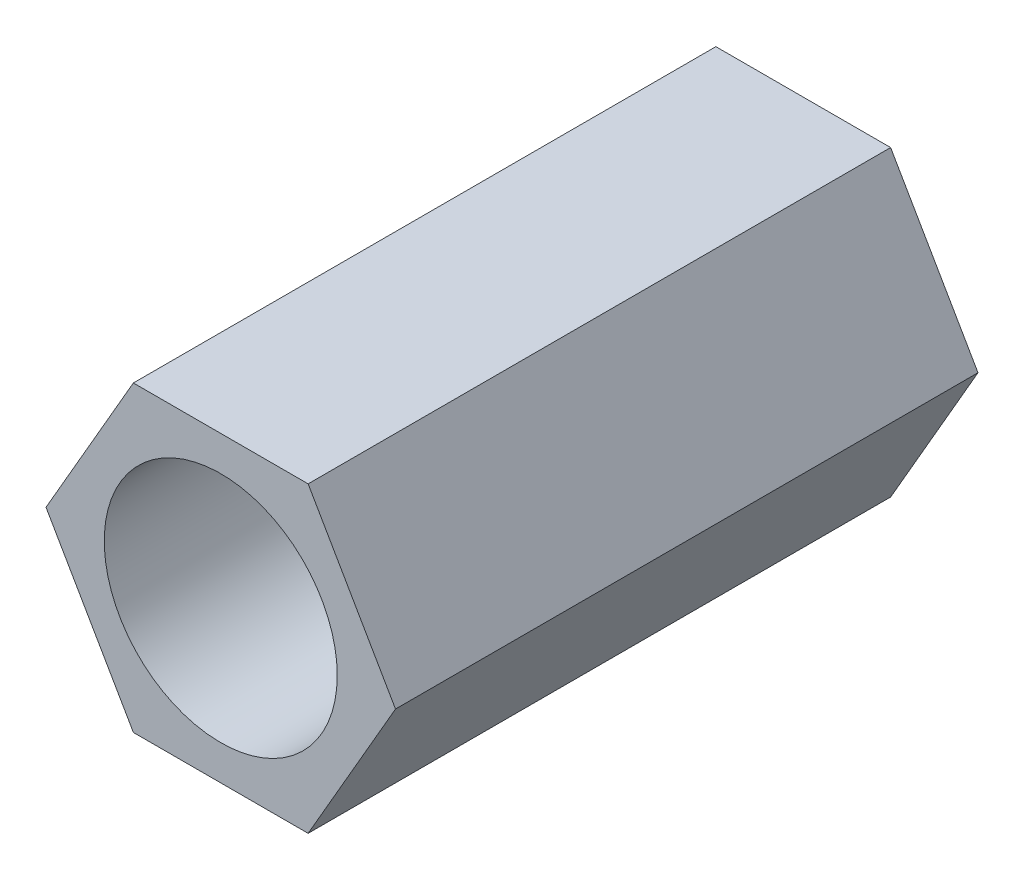
SolidWorks part; units mm, degrees
material "1.4310 (X10CrNi18-8)"
ref_plane "Front" through (0, 0, 0) normal (0, 0, 1) x (1, 0, 0)
ref_plane "Top" through (0, 0, 0) normal (0, 1, 0) x (1, 0, 0)
ref_plane "Right" through (0, 0, 0) normal (1, 0, 0) x (0, 0, -1)
sketch "Sketch1" plane through (0, 0, 0) normal (0, 0, 1) x (1, 0, 0)
  line L1 (-3, 0) -> (-1.5, -2.5981)
  line L2 (-1.5, -2.5981) -> (1.5, -2.5981)
  line L3 (1.5, -2.5981) -> (3, 0)
  line L4 (3, 0) -> (1.5, 2.5981)
  line L5 (1.5, 2.5981) -> (-1.5, 2.5981)
  line L6 (-1.5, 2.5981) -> (-3, 0)
  circle A0 centre (0, 0) radius 2
  circle A2 centre (0, 0) radius 2.5981 construction
  dimension "D1" = 4
  dimension "D2" = 3
extrude "Boss-Extrude1" add sketch "Sketch1" along normal blind 10
